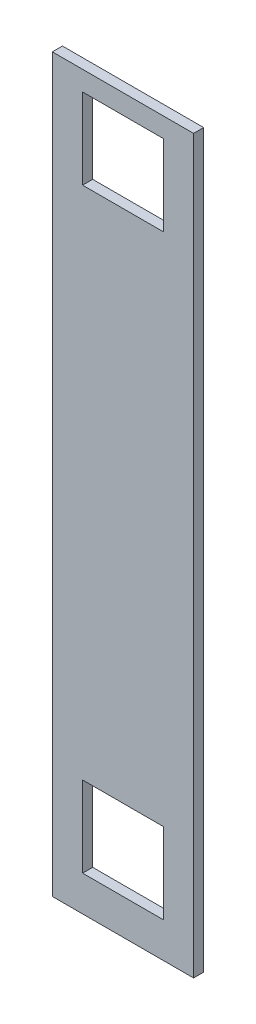
SolidWorks part; units mm, degrees
material "Oak"
ref_plane "Front Plane" through (0, 0, 0) normal (0, 0, 1) x (1, 0, 0)
ref_plane "Top Plane" through (0, 0, 0) normal (0, 1, 0) x (1, 0, 0)
ref_plane "Right Plane" through (0, 0, 0) normal (1, 0, 0) x (0, 0, -1)
sketch "Sketch1" plane through (0, 0, 0) normal (0, 0, 1) x (1, 0, 0)
  line L1 (-88.9, -460.375) -> (88.9, -460.375)
  line L2 (-88.9, -460.375) -> (-88.9, 460.375)
  line L3 (-88.9, 460.375) -> (88.9, 460.375)
  line L4 (88.9, -460.375) -> (88.9, 460.375)
  line L5 (-88.9, -460.375) -> (88.9, 460.375) construction
  line L6 (-88.9, 460.375) -> (88.9, -460.375) construction
  point P0 (0, 0)
  dimension "D1" = 920.75
  dimension "D2" = 177.8
extrude "Boss-Extrude1" add sketch "Sketch1" along normal blind 12.7
sketch "Sketch2" plane through (0, 0, 0) normal (0, 0, -1) x (-1, 0, 0)
  line L0 (-50.8, -415.925) -> (-88.9, -415.925) construction
  line L1 (-50.8, -314.325) -> (50.8, -314.325)
  line L2 (-50.8, -314.325) -> (-50.8, -415.925)
  line L3 (-50.8, -415.925) -> (50.8, -415.925)
  line L4 (50.8, -314.325) -> (50.8, -415.925)
  line L5 (-88.9, -460.375) -> (-88.9, 460.375) construction
  line L6 (50.8, -415.925) -> (88.9, -415.925) construction
  line L7 (88.9, 460.375) -> (88.9, -460.375) construction
  line L8 (88.9, -460.375) -> (-88.9, -460.375) construction
  line L9 (-50.8, 435.675) -> (-50.8, 334.075)
  line L10 (-50.8, 435.675) -> (50.8, 435.675)
  line L11 (50.8, 435.675) -> (50.8, 334.075)
  line L12 (-50.8, 334.075) -> (50.8, 334.075)
  dimension "D1" = 101.6
  dimension "D2" = 44.45
  dimension "D3" = 101.6
  dimension "D5" = 750
  dimension "D4" = 2
extrude "Cut-Extrude1" cut sketch "Sketch2" against normal up to next
